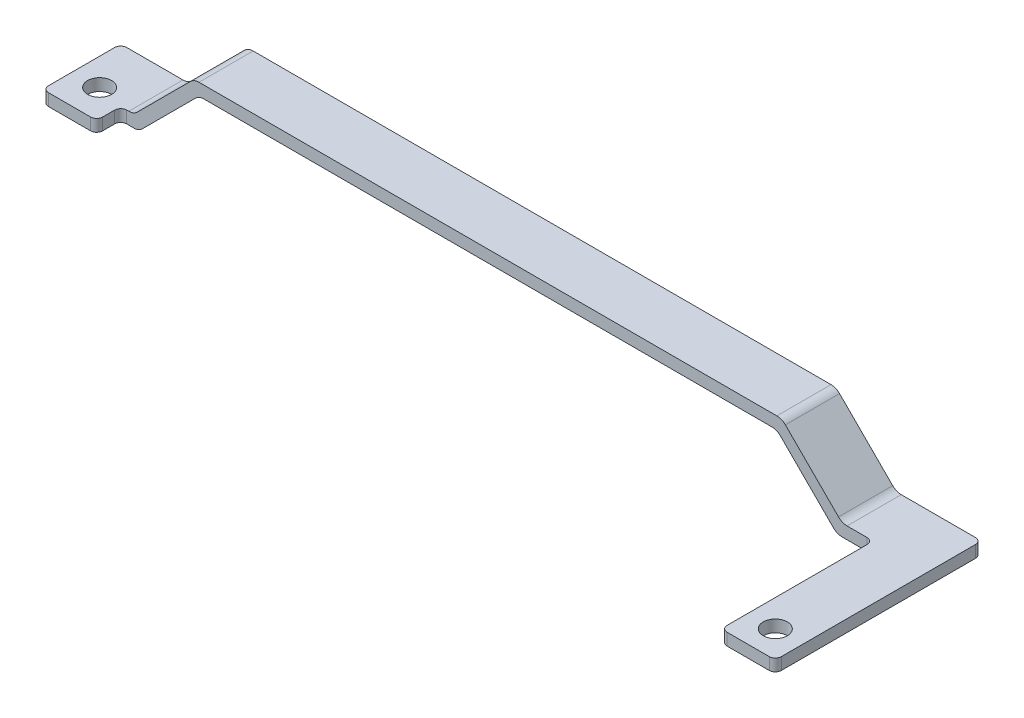
SolidWorks part; units mm, degrees
ref_plane "Front Plane" through (0, 0, 0) normal (0, 0, 1) x (1, 0, 0)
ref_plane "Top Plane" through (0, 0, 0) normal (0, 1, 0) x (1, 0, 0)
ref_plane "Right Plane" through (0, 0, 0) normal (1, 0, 0) x (0, 0, -1)
sketch "Sketch1" plane through (0, 0, 0) normal (0, 1, 0) x (1, 0, 0)
  line L9 (5.5, 20.76) -> (128.5, 20.76)
  line L10 (129.5, 19.76) -> (129.5, -3.5)
  line L11 (130.5, -4.5) -> (137.5, -4.5)
  line L12 (138.5, -3.5) -> (138.5, 28.76)
  line L13 (137.5, 29.76) -> (-3.5, 29.76)
  line L14 (0, 21.76) -> (0, 16.76) construction
  line L15 (4.5, 19.76) -> (4.5, 17.76)
  line L16 (134, 0) -> (129.5, 0) construction
  line L17 (134, 0) -> (138.5, 0) construction
  line L18 (134, 0) -> (134, -4.5) construction
  line L19 (0, 21.76) -> (-4.5, 21.76) construction
  line L20 (3.5, 16.76) -> (-3.5, 16.76)
  line L22 (-4.5, 28.76) -> (-4.5, 17.76)
  line L23 (-4.5, 17.76) -> (-4.5, 16.76) construction
  line L24 (-3.5, 16.76) -> (-4.5, 16.76) construction
  circle A0 centre (0, 21.76) radius 2
  circle A1 centre (134, 0) radius 2
  arc A2 (129.5, -3.5) -> (130.5, -4.5) centre (130.5, -3.5) ccw
  arc A3 (137.5, -4.5) -> (138.5, -3.5) centre (137.5, -3.5) ccw
  arc A4 (138.5, 28.76) -> (137.5, 29.76) centre (137.5, 28.76) ccw
  arc A5 (128.5, 20.76) -> (129.5, 19.76) centre (128.5, 19.76) cw
  arc A7 (-4.5, 28.76) -> (-3.5, 29.76) centre (-3.5, 28.76) cw
  arc A8 (4.5, 17.76) -> (3.5, 16.76) centre (3.5, 17.76) cw
  arc A9 (-3.5, 16.76) -> (-4.5, 17.76) centre (-3.5, 17.76) cw
  arc A10 (5.5, 20.76) -> (4.5, 19.76) centre (5.5, 19.76) ccw
  point P0 (0, 21.76)
  point P1 (134, 0)
  point P24 (138.5, 29.76)
  point P29 (4.5, 20.76)
  point P38 (4.5, 16.76)
  point P41 (-4.5, 16.76)
  dimension "D3" = 4
  dimension "D4" = 4
  dimension "D7" = 1
  dimension "D6" = 1
  dimension "D11" = 1
  dimension "D13" = 4.5
  dimension "D14" = 1
  dimension "D1" = 134
  dimension "D2" = 21.76
  dimension "D5" = 4.5
  dimension "D8" = 9
  dimension "D9" = 4
  dimension "D10" = 9
  dimension "D12" = 5
extrude "Boss-Extrude1" add sketch "Sketch1" along normal blind 12
sketch "Sketch2" plane through (0, 0, 4.5) normal (0, 0, 1) x (1, 0, 0)
  line L0 (-4.5, 12) -> (-4.5, 2)
  line L1 (-4.5, 12) -> (-4.5, 0) construction
  line L2 (-4.5, 2) -> (6.6716, 2)
  line L3 (6.6716, 2) -> (16.6716, 12)
  line L4 (5.5, 12) -> (128.5, 12) construction
  line L5 (16.6716, 12) -> (-4.5, 12)
  line L6 (7.5, 0) -> (123.5, 0)
  line L7 (5.5, 0) -> (128.5, 0) construction
  line L8 (123.5, 0) -> (113.5, 10)
  line L9 (113.5, 10) -> (17.5, 10)
  line L10 (17.5, 10) -> (7.5, 0)
  line L11 (114.3284, 12) -> (124.3284, 2)
  line L13 (124.3284, 2) -> (138.5, 2)
  line L14 (138.5, 12) -> (138.5, 0) construction
  line L15 (138.5, 2) -> (138.5, 12)
  line L16 (138.5, 12) -> (114.3284, 12)
  line L17 (130.5, 0) -> (137.5, 0) construction
  dimension "D1" = 2
  dimension "D2" = 2
  dimension "D3" = 2
  dimension "D4" = 2
  dimension "D5" = 2
  dimension "D6" = 12
  dimension "D7" = 45
  dimension "D8" = 45
  dimension "D9" = 15
extrude "Cut-Extrude1" cut sketch "Sketch2" against normal through all
fillet "Fillet1" radius 2 8 edges at (123.5, 0, -25.26) (124.3284, 2, -25.26) (114.3284, 12, -25.26) (113.5, 10, -25.26) (17.5, 10, -25.26) (7.5, 0, -25.26) (6.6716, 2, -25.26) (16.6716, 12, -25.26)
